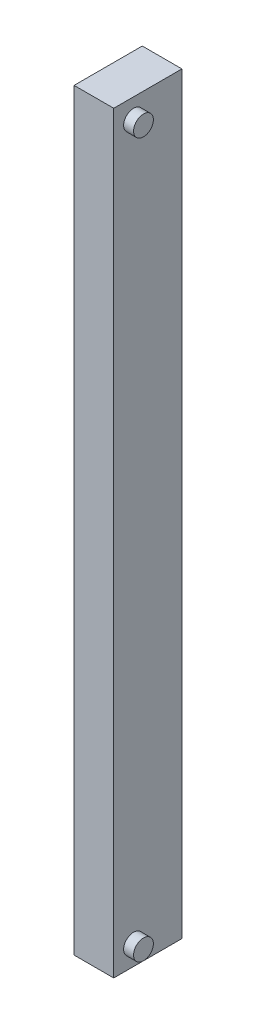
SolidWorks part; units mm, degrees
ref_plane "Front Plane" through (0, 0, 0) normal (0, 0, 1) x (1, 0, 0)
ref_plane "Top Plane" through (0, 0, 0) normal (0, 1, 0) x (1, 0, 0)
ref_plane "Right Plane" through (0, 0, 0) normal (1, 0, 0) x (0, 0, -1)
sketch "Sketch1" plane through (0, 0, 0) normal (0, 1, 0) x (1, 0, 0)
  line L1 (0, 0) -> (25.4, 0)
  line L2 (0, 0) -> (0, 25.4)
  line L3 (0, 25.4) -> (25.4, 25.4)
  line L4 (25.4, 0) -> (25.4, 25.4)
  dimension "D1" = 25.4
  dimension "D2" = 25.4
extrude "Boss-Extrude1" add sketch "Sketch1" along normal blind 482.6
sketch "Sketch2" plane through (25.4, 0, 0) normal (1, 0, 0) x (0, 0, -1)
  line L0 (0, 482.6) -> (25.4, 482.6) construction
  line L1 (0, 482.6) -> (0, 0) construction
  circle A0 centre (12.7, 469.9) radius 6.35
  dimension "D1" = 12.7
  dimension "D2" = 12.7
extrude "Boss-Extrude2" add sketch "Sketch2" along normal blind 6.35
sketch "Sketch3" plane through (25.4, 0, 0) normal (1, 0, 0) x (0, 0, -1)
  line L0 (25.4, 482.6) -> (25.4, 0) construction
  line L1 (0, 0) -> (25.4, 0) construction
  circle A0 centre (12.7, 12.7) radius 6.35
  dimension "D1" = 12.7
  dimension "D2" = 12.7
extrude "Boss-Extrude3" add sketch "Sketch3" along normal blind 6.35
sketch "Sketch4" plane through (0, 0, -25.4) normal (0, 0, -1) x (-1, 0, 0)
  line L1 (0, 0) -> (-25.4, 0)
  line L2 (0, 0) -> (0, 482.6)
  line L3 (0, 482.6) -> (-25.4, 482.6)
  line L4 (-25.4, 0) -> (-25.4, 482.6)
extrude "Boss-Extrude4" add sketch "Sketch4" along normal blind 18.288
